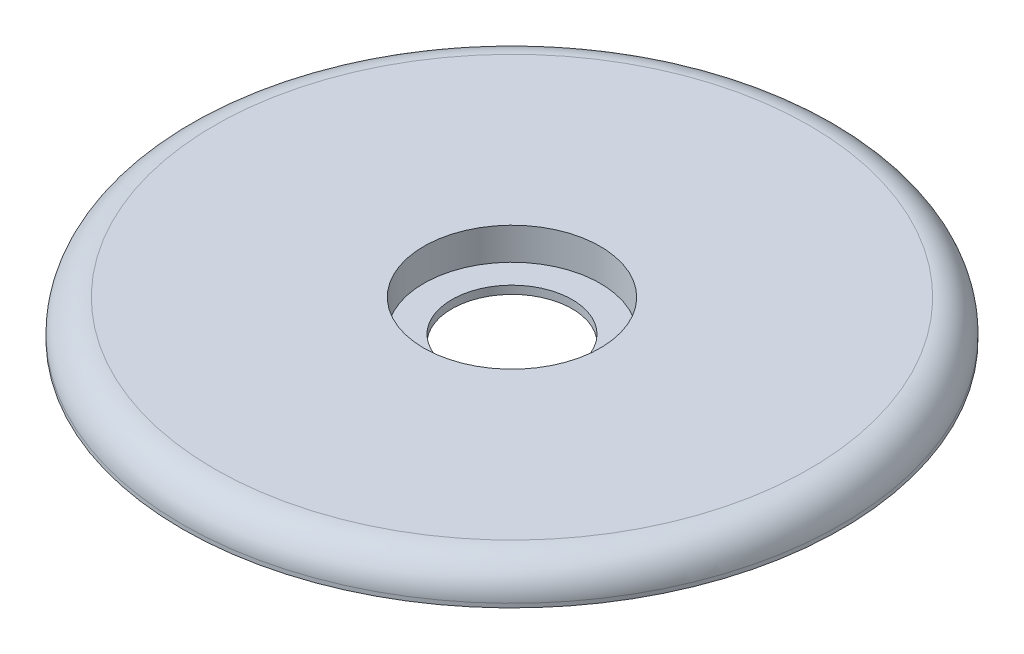
SolidWorks part; units mm, degrees
ref_plane "Front Plane" through (0, 0, 0) normal (0, 0, 1) x (1, 0, 0)
ref_plane "Top Plane" through (0, 0, 0) normal (0, 1, 0) x (1, 0, 0)
ref_plane "Right Plane" through (0, 0, 0) normal (1, 0, 0) x (0, 0, -1)
sketch "Sketch1" plane through (0, 0, 0) normal (0, 1, 0) x (1, 0, 0)
  circle A0 centre (0, 0) radius 41.1
  dimension "D1" = 82.2
extrude "Boss-Extrude1" add sketch "Sketch1" along normal blind 4.5
sketch "Sketch5" plane through (0, 0, 0) normal (0, -1, 0) x (1, 0, 0)
  circle A0 centre (0, 0) radius 38.4
extrude "Boss-Extrude3" add sketch "Sketch5" along normal blind 0.5
sketch "Sketch2" plane through (0, 4.5, 0) normal (0, 1, 0) x (1, 0, 0)
  circle A0 centre (0, 0) radius 11
  circle A1 centre (0, 0) radius 4.5
  dimension "D1" = 22
extrude "Cut-Extrude1" cut sketch "Sketch2" against normal blind 4 contours A0 A1 | A1
sketch "Sketch3" plane through (0, 0.5, 0) normal (0, 1, 0) x (1, 0, 0)
  circle A0 centre (0, 0) radius 7.5
  dimension "D1" = 15
extrude "Cut-Extrude2" cut sketch "Sketch3" against normal through all
fillet "Fillet1" radius 4 1 edges at (0, 4.5, 41.1)
